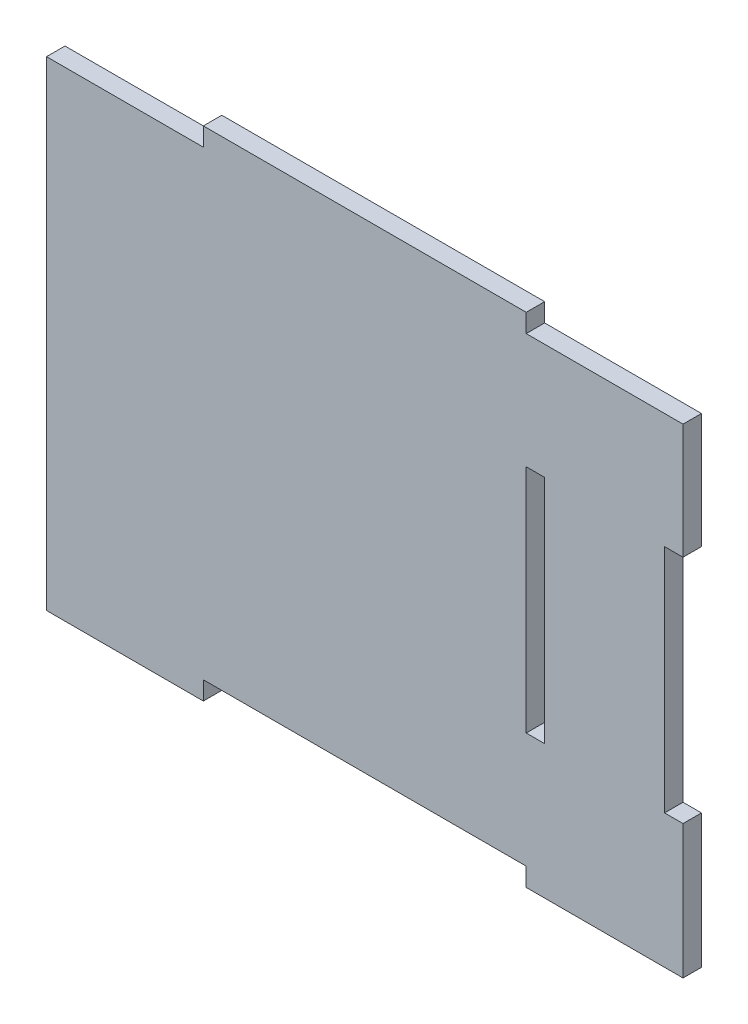
SolidWorks part; units mm, degrees
ref_plane "Спереди" through (0, 0, 0) normal (0, 0, 1) x (1, 0, 0)
ref_plane "Сверху" through (0, 0, 0) normal (0, 1, 0) x (1, 0, 0)
ref_plane "Справа" through (0, 0, 0) normal (1, 0, 0) x (0, 0, -1)
sketch "Эскиз1" plane through (0, 0, 0) normal (0, 0, 1) x (1, 0, 0)
  line L0 (-35.3804, 50.6074) -> (-65.3804, 50.6074)
  line L1 (34.6196, -49.3926) -> (-35.3804, -49.3926)
  line L2 (64.6196, -24.3926) -> (64.6196, 25.6074)
  line L3 (64.6196, 50.6074) -> (34.6196, 50.6074)
  line L6 (-65.3804, -53.3926) -> (-35.3804, -53.3926)
  line L7 (-35.3804, -49.3926) -> (-35.3804, -53.3926)
  line L8 (64.6196, -53.3926) -> (34.6196, -53.3926)
  line L9 (34.6196, -49.3926) -> (34.6196, -53.3926)
  line L10 (-35.3804, 50.6074) -> (-35.3804, 54.6074)
  line L11 (-35.3804, 54.6074) -> (34.6196, 54.6074)
  line L12 (34.6196, 50.6074) -> (34.6196, 54.6074)
  line L13 (34.6196, 25.6074) -> (38.6196, 25.6074)
  line L14 (34.6196, 25.6074) -> (34.6196, -24.3926)
  line L15 (34.6196, -24.3926) -> (38.6196, -24.3926)
  line L16 (38.6196, 25.6074) -> (38.6196, -24.3926)
  line L17 (64.6196, 50.6074) -> (68.6196, 50.6074)
  line L18 (64.6196, 25.6074) -> (68.6196, 25.6074)
  line L19 (68.6196, 50.6074) -> (68.6196, 25.6074)
  line L20 (64.6196, -24.3926) -> (68.6196, -24.3926)
  line L21 (64.6196, -53.3926) -> (68.6196, -53.3926)
  line L22 (68.6196, -24.3926) -> (68.6196, -53.3926)
  line L24 (-65.3804, 50.6074) -> (-69.3804, 50.6074)
  line L26 (-65.3804, -53.3926) -> (-69.3804, -53.3926)
  line L27 (-69.3804, 50.6074) -> (-69.3804, -53.3926)
  dimension "D1" = 30
  dimension "D2" = 130
  dimension "D3" = 50
  dimension "D4" = 26
  dimension "D5" = 25
  dimension "D6" = 100
  dimension "D7" = 4
  dimension "D8" = 70
  dimension "D9" = 4
extrude "Бобышка-Вытянуть1" add sketch "Эскиз1" along normal blind 4
